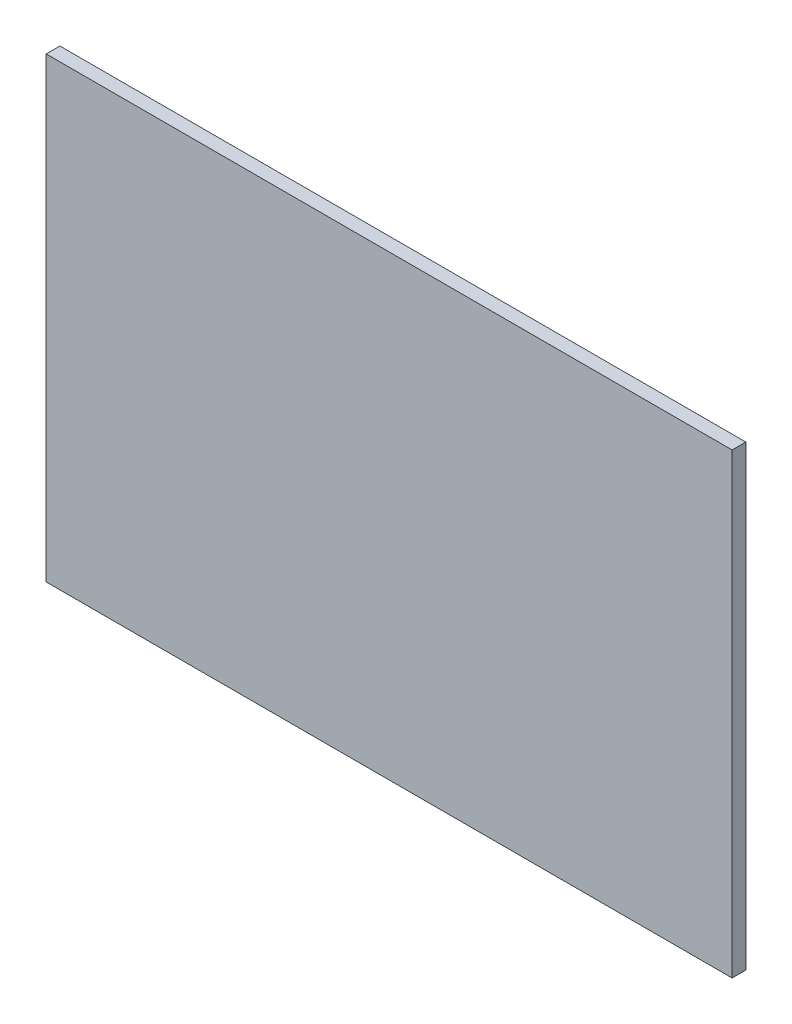
SolidWorks part; units mm, degrees
ref_plane "Plan de face" through (0, 0, 0) normal (0, 0, 1) x (1, 0, 0)
ref_plane "Plan de dessus" through (0, 0, 0) normal (0, 1, 0) x (1, 0, 0)
ref_plane "Plan de droite" through (0, 0, 0) normal (1, 0, 0) x (0, 0, -1)
sketch "Esquisse1" plane through (0, 0, 0) normal (0, 0, 1) x (1, 0, 0)
  line L1 (-75, 44.542) -> (75, 44.542)
  line L2 (-75, 44.542) -> (-75, -55.458)
  line L3 (-75, -55.458) -> (75, -55.458)
  line L4 (75, 44.542) -> (75, -55.458)
  dimension "D1" = 150
  dimension "D2" = 75
  dimension "D3" = 100
extrude "Boss.-Extru.1" add sketch "Esquisse1" along normal blind 3
